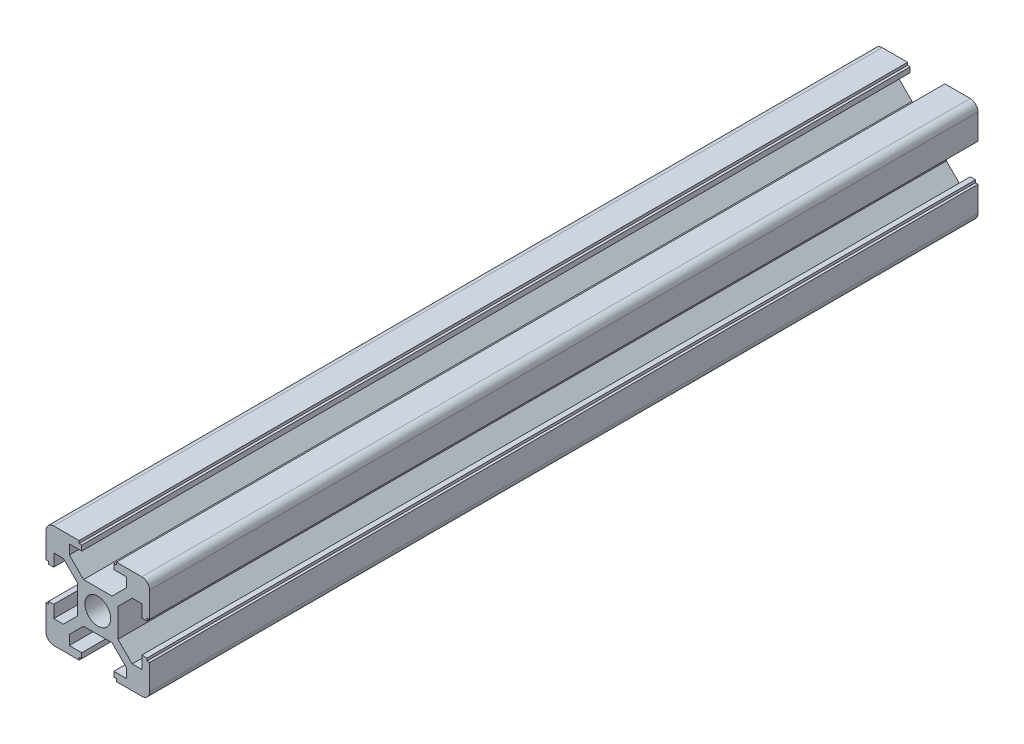
SolidWorks part; units mm, degrees
ref_plane "前视基准面" through (0, 0, 0) normal (0, 0, 1) x (1, 0, 0)
ref_plane "上视基准面" through (0, 0, 0) normal (0, 1, 0) x (1, 0, 0)
ref_plane "右视基准面" through (0, 0, 0) normal (1, 0, 0) x (0, 0, -1)
other "Configuration Table"
sketch "草图2" plane through (0, 0, 0) normal (0, 0, 1) x (1, 0, 0)
  line L0 (-3.6, 10) -> (-3.6, 9.5)
  line L1 (-3.6, 9.5) -> (-3.1, 9.5)
  line L2 (-3.1, 9.5) -> (-3.1, 8.5)
  line L3 (-3.1, 8.5) -> (-5.5, 8.5)
  line L4 (-8.5, -10) -> (-3.6, -10)
  line L5 (-10, -8.5) -> (-10, -3.6)
  line L6 (8.5, 10) -> (3.6, 10)
  line L7 (10, 8.5) -> (10, 3.6)
  line L8 (0, 14.8756) -> (0, 0) construction
  line L9 (0, 0) -> (14.1675, 0) construction
  line L10 (-5.5, 8.5) -> (-5.5, 6.65)
  line L11 (-5.5, 6.65) -> (-2.75, 3.9)
  line L12 (-2.75, 3.9) -> (2.75, 3.9)
  line L13 (5.5, 6.65) -> (2.75, 3.9)
  line L14 (5.5, 8.5) -> (5.5, 6.65)
  line L15 (3.1, 8.5) -> (5.5, 8.5)
  line L16 (3.1, 9.5) -> (3.1, 8.5)
  line L17 (3.6, 9.5) -> (3.1, 9.5)
  line L18 (3.6, 10) -> (3.6, 9.5)
  line L19 (-3.6, 10) -> (-8.5, 10)
  line L20 (10, 3.6) -> (9.5, 3.6)
  line L21 (9.5, 3.6) -> (9.5, 3.1)
  line L22 (9.5, 3.1) -> (8.5, 3.1)
  line L23 (8.5, 3.1) -> (8.5, 5.5)
  line L24 (8.5, 5.5) -> (6.65, 5.5)
  line L25 (6.65, 5.5) -> (3.9, 2.75)
  line L26 (3.9, 2.75) -> (3.9, -2.75)
  line L27 (6.65, -5.5) -> (3.9, -2.75)
  line L28 (8.5, -5.5) -> (6.65, -5.5)
  line L29 (8.5, -3.1) -> (8.5, -5.5)
  line L30 (9.5, -3.1) -> (8.5, -3.1)
  line L31 (9.5, -3.6) -> (9.5, -3.1)
  line L32 (10, -3.6) -> (9.5, -3.6)
  line L33 (3.6, -10) -> (3.6, -9.5)
  line L34 (3.6, -9.5) -> (3.1, -9.5)
  line L35 (3.1, -9.5) -> (3.1, -8.5)
  line L36 (3.1, -8.5) -> (5.5, -8.5)
  line L37 (5.5, -8.5) -> (5.5, -6.65)
  line L38 (5.5, -6.65) -> (2.75, -3.9)
  line L39 (2.75, -3.9) -> (-2.75, -3.9)
  line L40 (-5.5, -6.65) -> (-2.75, -3.9)
  line L41 (-5.5, -8.5) -> (-5.5, -6.65)
  line L42 (-3.1, -8.5) -> (-5.5, -8.5)
  line L43 (-3.1, -9.5) -> (-3.1, -8.5)
  line L44 (-3.6, -9.5) -> (-3.1, -9.5)
  line L45 (-3.6, -10) -> (-3.6, -9.5)
  line L46 (-10, -3.6) -> (-9.5, -3.6)
  line L47 (-9.5, -3.6) -> (-9.5, -3.1)
  line L48 (-9.5, -3.1) -> (-8.5, -3.1)
  line L49 (-8.5, -3.1) -> (-8.5, -5.5)
  line L50 (-8.5, -5.5) -> (-6.65, -5.5)
  line L51 (-6.65, -5.5) -> (-3.9, -2.75)
  line L52 (-3.9, -2.75) -> (-3.9, 2.75)
  line L53 (-6.65, 5.5) -> (-3.9, 2.75)
  line L54 (-8.5, 5.5) -> (-6.65, 5.5)
  line L55 (-8.5, 3.1) -> (-8.5, 5.5)
  line L56 (-9.5, 3.1) -> (-8.5, 3.1)
  line L57 (-9.5, 3.6) -> (-9.5, 3.1)
  line L58 (-10, 3.6) -> (-9.5, 3.6)
  line L59 (3.6, -10) -> (8.5, -10)
  line L60 (-10, 3.6) -> (-10, 8.5)
  line L61 (10, -3.6) -> (10, -8.5)
  circle A0 centre (0, 0) radius 2.5
  arc A1 (-10, 8.5) -> (-8.5, 10) centre (-8.5, 8.5) cw
  arc A2 (10, 8.5) -> (8.5, 10) centre (8.5, 8.5) ccw
  arc A3 (-8.5, -10) -> (-10, -8.5) centre (-8.5, -8.5) cw
  arc A4 (8.5, -10) -> (10, -8.5) centre (8.5, -8.5) ccw
  point P0 (-10, 0)
  point P1 (10, 0)
  point P2 (0, 10)
  point P3 (0, -10)
  point P4 (0, 0)
  point P5 (-10, -10)
  point P6 (10, -10)
  point P7 (10, 10)
  point P8 (-10, 10)
  point P36 (-10, 10)
  point P39 (10, 10)
  dimension "D1" = 11
  dimension "D2" = 20
  dimension "D3" = 6.2
  dimension "D4" = 7.2
  dimension "D5" = 6.1
  dimension "D6" = 5
  dimension "D7" = 1.5
  dimension "D8" = 45
  dimension "D9" = 0.5
  dimension "D10" = 1
  dimension "D11" = 5.5
extrude "凸台-拉伸1" add sketch "草图2" along normal blind 160
